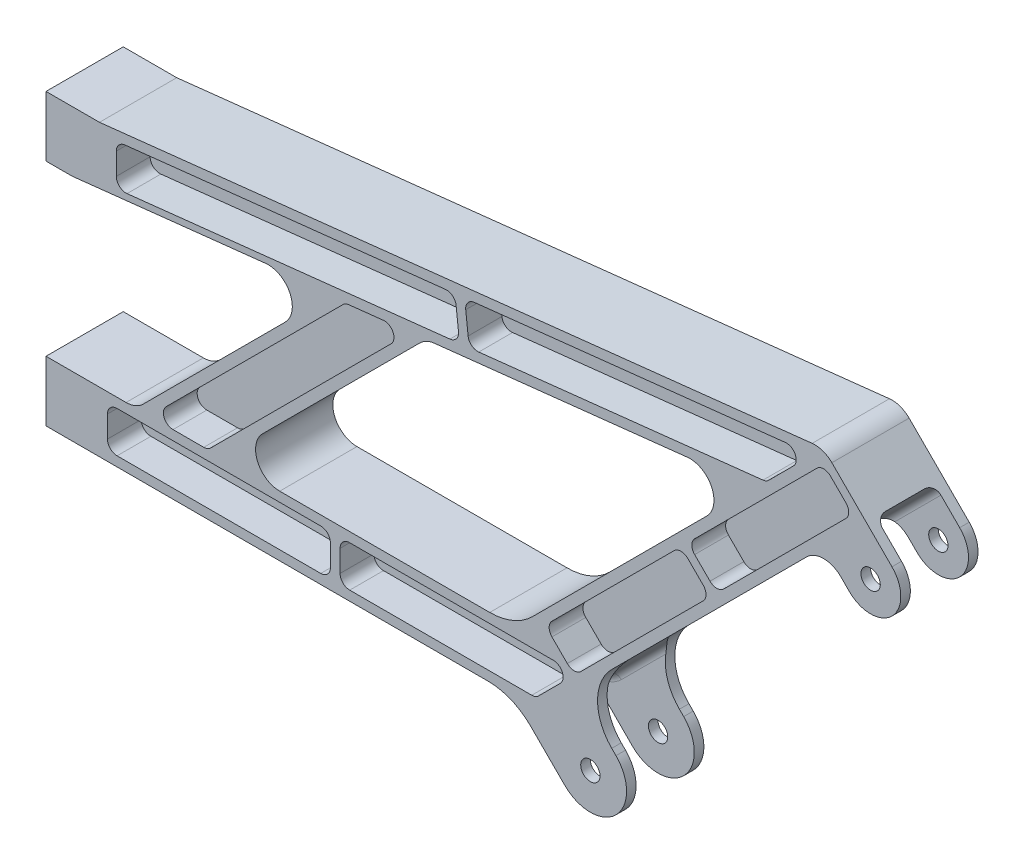
SolidWorks part; units mm, degrees
material "6061-T6 (SS)"
ref_plane "Front Plane" through (0, 0, 0) normal (0, 0, 1) x (1, 0, 0)
ref_plane "Top Plane" through (0, 0, 0) normal (0, 1, 0) x (1, 0, 0)
ref_plane "Right Plane" through (0, 0, 0) normal (1, 0, 0) x (0, 0, -1)
sketch "Sketch1" plane through (0, 0, 0) normal (0, 0, 1) x (1, 0, 0)
  line L1 (-157.7639, -90.8401) -> (-244.7728, -90.8401)
  line L2 (-67.8181, -11.2496) -> (-140.0863, -83.5177)
  line L3 (-16.0497, 33.7315) -> (8.8396, 8.8381)
  line L4 (-12.3744, -5.3033) -> (-8.8388, -8.8388)
  line L5 (-26.5165, -5.3033) -> (-107.2487, -86.0355)
  line L6 (-140.8326, -123.1624) -> (-126.6942, -137.3008)
  line L7 (-158.5102, -115.8401) -> (-341.1373, -115.8401)
  line L8 (-341.1373, -115.8401) -> (-341.1373, -90.8401)
  line L9 (-308.4124, -90.8401) -> (-341.1373, -90.8401)
  line L11 (-341.5776, -20.8403) -> (-331.2717, -20.8403)
  line L12 (-341.5776, -20.8403) -> (-341.5776, 4.1597)
  line L13 (-341.5776, 4.1597) -> (-319.4176, 4.1597)
  line L14 (-107.2487, -114.3198) -> (-105.481, -116.0876)
  line L15 (-319.4176, 4.1597) -> (-24.2138, 36.6012)
  line L17 (-301.3413, -87.9111) -> (-242.4814, -29.0512)
  line L18 (-75.9816, 5.7616) -> (-180.7131, -5.7479)
  line L19 (-251.8438, -73.769) -> (-186.6918, -8.6169)
  line L20 (-250.6448, -12.04) -> (-330.1793, -20.7804)
  arc A4 (8.8388, -8.8388) -> (8.8396, 8.8381) centre (0, 0) ccw
  arc A5 (-8.8388, -8.8388) -> (8.8388, -8.8388) centre (0, 0) ccw
  arc A6 (-12.3744, -5.3033) -> (-26.5165, -5.3033) centre (-19.4454, -12.3744) ccw
  arc A7 (-107.2487, -86.0355) -> (-107.2487, -114.3198) centre (-93.1066, -100.1777) ccw
  arc A8 (-105.481, -137.3008) -> (-105.481, -116.0876) centre (-116.0876, -126.6942) ccw
  arc A9 (-126.6942, -137.3008) -> (-105.481, -137.3008) centre (-116.0876, -126.6942) ccw
  circle A12 centre (-116.0876, -126.6942) radius 4
  circle A13 centre (0, 0) radius 4
  arc A15 (-158.5102, -115.8401) -> (-140.8326, -123.1624) centre (-158.5102, -140.8401) cw
  arc A16 (-157.7639, -90.8401) -> (-140.0863, -83.5177) centre (-157.7639, -65.8401) ccw
  arc A20 (-67.8181, -11.2496) -> (-75.9816, 5.7616) centre (-74.8892, -4.1785) ccw
  arc A21 (-16.0497, 33.7315) -> (-24.2138, 36.6012) centre (-23.1214, 26.661) ccw
  arc A22 (-186.6918, -8.6169) -> (-180.7131, -5.7479) centre (-179.6207, -15.688) cw
  arc A23 (-244.7728, -90.8401) -> (-251.8438, -73.769) centre (-244.7728, -80.8401) cw
  arc A24 (-330.1793, -20.7804) -> (-331.2717, -20.8403) centre (-331.2717, -10.8403) cw
  arc A25 (-308.4124, -90.8401) -> (-301.3413, -87.9111) centre (-308.4124, -80.8401) ccw
  arc A26 (-250.6448, -12.04) -> (-242.4814, -29.0512) centre (-249.5525, -21.9802) cw
  dimension "D2" = 25
  dimension "D3" = 25
  dimension "D7" = 10
  dimension "D6" = 25
  dimension "D1" = 25
  dimension "D4" = 25
  dimension "D5" = 25
  dimension "D8" = 119.9998
extrude "Boss-Extrude1" add sketch "Sketch1" along normal blind 32
sketch "Sketch2" plane through (0, 0, 32) normal (0, 0, 1) x (1, 0, 0)
  line L0 (-107.2487, -86.0355) -> (-26.5165, -5.3033) construction
  line L1 (-137.5386, -110.6685) -> (-128.5386, -101.6685)
  line L2 (-131.367, -94.8401) -> (-215.77, -94.8401)
  line L3 (-67.8181, -11.2496) -> (-140.0863, -83.5177) construction
  line L4 (-107.2487, -86.0355) -> (-26.5165, -5.3033)
  line L5 (-67.8181, -11.2496) -> (-140.0863, -83.5177)
  line L6 (-22.272, 28.6397) -> (-72.893, -21.9813)
  line L7 (-119.9767, -93.1066) -> (-69.3575, -42.4874)
  line L8 (-131.9975, -86.7426) -> (-125.6335, -93.1066)
  line L9 (-10.2515, 22.275) -> (-16.6149, 28.6394)
  line L10 (-64.9897, -14.078) -> (-137.2579, -86.3462) construction
  line L11 (-110.0772, -83.2071) -> (-29.3449, -2.4749) construction
  line L12 (-341.1373, -115.8401) -> (-158.5102, -115.8401) construction
  line L13 (-341.1373, -115.8401) -> (-158.5102, -115.8401)
  line L14 (-312.1373, -111.8401) -> (-227.77, -111.8401)
  line L15 (-341.1373, -111.8401) -> (-158.5102, -111.8401) construction
  line L16 (-341.1373, -90.8401) -> (-341.1373, -115.8401) construction
  line L17 (-316.1373, -98.8401) -> (-316.1373, -107.8401)
  line L18 (-157.7639, -90.8401) -> (-244.7728, -90.8401) construction
  line L19 (8.8396, 8.8381) -> (-16.0497, 33.7315) construction
  line L20 (-140.8326, -123.1624) -> (-126.6942, -137.3008) construction
  line L21 (-65.1149, -38.2448) -> (-77.1357, -26.224) construction
  line L22 (-72.893, -27.6382) -> (-66.5291, -34.0022)
  line L23 (-75.7215, -30.4666) -> (-69.3575, -36.8306)
  line L24 (-81.3783, -30.4666) -> (-131.9975, -81.0858)
  line L25 (-60.8722, -34.0022) -> (-10.2517, 16.6183)
  line L26 (-221.77, -94.8401) -> (-221.77, -111.8401) construction
  line L27 (-219.77, -98.8401) -> (-219.77, -107.8401)
  line L28 (-223.77, -98.8401) -> (-223.77, -107.8401)
  line L29 (-215.77, -111.8401) -> (-140.367, -111.8401)
  line L30 (-227.77, -94.8401) -> (-312.1373, -94.8401)
  line L38 (-308.8907, 1.2925) -> (-176.1091, 15.8845)
  line L39 (-24.2138, 36.6012) -> (-319.4176, 4.1597) construction
  line L40 (-308.0168, -15.7138) -> (-174.2521, -1.0137)
  line L41 (-75.9816, 5.7616) -> (-180.7131, -5.7479) construction
  line L42 (-312.4538, -2.6836) -> (-312.4538, -11.7378)
  line L43 (-32.0118, 24.5568) -> (-42.1838, 14.3847)
  line L44 (-170.145, 16.5399) -> (-168.288, -0.3583) construction
  line L45 (-171.6961, 12.3454) -> (-170.713, 3.3993)
  line L46 (-167.7201, 12.7824) -> (-166.7369, 3.8362)
  line L47 (-164.181, 17.1954) -> (-35.2771, 31.3613)
  line L48 (-162.3239, 0.2971) -> (-44.5753, 13.2371)
  line L49 (-218.5658, -10.7925) -> (-291.7849, -84.0116)
  line L50 (-242.4814, -29.0512) -> (-301.3413, -87.9111) construction
  line L51 (-198.6096, -14.8779) -> (-273.4002, -89.6685)
  line L52 (-186.6918, -8.6169) -> (-251.8438, -73.769) construction
  line L53 (-216.1743, -9.6449) -> (-201.875, -8.0734)
  line L54 (-288.9565, -90.8401) -> (-276.2286, -90.8401)
  line L55 (-341.5776, 4.1597) -> (-341.5776, -20.8403) construction
  arc A0 (-22.272, 28.6397) -> (-16.6149, 28.6394) centre (-19.4436, 25.8113) cw
  arc A1 (-10.2517, 16.6183) -> (-10.2515, 22.275) centre (-13.0801, 19.4468) ccw
  arc A2 (-119.9767, -93.1066) -> (-125.6335, -93.1066) centre (-122.8051, -90.2782) cw
  arc A3 (-131.9975, -81.0858) -> (-131.9975, -86.7426) centre (-129.169, -83.9142) ccw
  arc A4 (-312.1373, -111.8401) -> (-316.1373, -107.8401) centre (-312.1373, -107.8401) cw
  arc A5 (-312.1373, -94.8401) -> (-316.1373, -98.8401) centre (-312.1373, -98.8401) ccw
  arc A6 (-140.367, -111.8401) -> (-137.5386, -110.6685) centre (-140.367, -107.8401) ccw
  arc A7 (-128.5386, -101.6685) -> (-131.367, -94.8401) centre (-131.367, -98.8401) ccw
  arc A8 (-75.7215, -30.4666) -> (-81.3783, -30.4666) centre (-78.5499, -33.295) ccw
  arc A9 (-69.3575, -36.8306) -> (-69.3575, -42.4874) centre (-72.1859, -39.659) cw
  arc A10 (-66.5291, -34.0022) -> (-60.8722, -34.0022) centre (-63.7006, -31.1737) ccw
  arc A11 (-72.893, -27.6382) -> (-72.893, -21.9813) centre (-70.0646, -24.8098) cw
  arc A12 (-223.77, -107.8401) -> (-227.77, -111.8401) centre (-227.77, -107.8401) cw
  arc A13 (-219.77, -107.8401) -> (-215.77, -111.8401) centre (-215.77, -107.8401) ccw
  arc A14 (-219.77, -98.8401) -> (-215.77, -94.8401) centre (-215.77, -98.8401) cw
  arc A15 (-223.77, -98.8401) -> (-227.77, -94.8401) centre (-227.77, -98.8401) ccw
  arc A20 (-44.5753, 13.2371) -> (-42.1838, 14.3847) centre (-45.0122, 17.2132) ccw
  arc A21 (-35.2771, 31.3613) -> (-32.0118, 24.5568) centre (-34.8402, 27.3852) cw
  arc A22 (-166.7369, 3.8362) -> (-162.3239, 0.2971) centre (-162.7609, 4.2732) ccw
  arc A23 (-167.7201, 12.7824) -> (-164.181, 17.1954) centre (-163.744, 13.2193) cw
  arc A24 (-170.713, 3.3993) -> (-174.2521, -1.0137) centre (-174.6891, 2.9623) cw
  arc A25 (-171.6961, 12.3454) -> (-176.1091, 15.8845) centre (-175.6722, 11.9085) ccw
  arc A26 (-308.0168, -15.7138) -> (-312.4538, -11.7378) centre (-308.4538, -11.7378) cw
  arc A27 (-308.8907, 1.2925) -> (-312.4538, -2.6836) centre (-308.4538, -2.6836) ccw
  arc A28 (-198.6096, -14.8779) -> (-201.875, -8.0734) centre (-201.438, -12.0495) ccw
  arc A29 (-218.5658, -10.7925) -> (-216.1743, -9.6449) centre (-215.7374, -13.6209) cw
  arc A30 (-273.4002, -89.6685) -> (-276.2286, -90.8401) centre (-276.2286, -86.8401) cw
  arc A31 (-288.9565, -90.8401) -> (-291.7849, -84.0116) centre (-288.9565, -86.8401) cw
  point P34 (-316.1373, -111.8401)
  point P53 (-78.5499, -27.6382)
  point P58 (-63.7006, -36.8306)
  point P69 (-223.77, -111.8401)
  point P72 (-219.77, -111.8401)
  point P75 (-219.77, -94.8401)
  point P78 (-223.77, -94.8401)
  point P117 (-166.3, -0.1398)
  point P120 (-168.157, 16.7584)
  point P123 (-170.276, -0.5768)
  point P126 (-172.1331, 16.3215)
  dimension "D2" = 4
  dimension "D6" = 4
  dimension "D11" = 4
  dimension "D13" = 4
  dimension "D16" = 4
  dimension "D22" = 4
  dimension "D19" = 4
  dimension "D4" = 25
  dimension "D5" = 4
  dimension "D7" = 4
  dimension "D8" = 4
  dimension "D9" = 32
  dimension "D10" = 2
  dimension "D12" = 2
  dimension "D14" = 4
  dimension "D15" = 4
  dimension "D17" = 4
  dimension "D18" = 4
  dimension "D20" = 4
  dimension "D21" = 2
  dimension "D23" = 4
  dimension "D1" = 4
  dimension "D3" = 4
extrude "Cut-Extrude1" cut sketch "Sketch2" against normal blind 14 contours L38 A27 L42 A26 L40 A24 L45 A25 | A23 L46 A22 L48 A20 L43 A21 L47 | A31 L54 A30 L51 A28 L53 A29 L49 | A11 L22 A10 L25 A1 L9 A0 L6 | A9 L23 A8 L24 A3 L8 A2 L7 | A14 L27 A13 L29 A6 L1 A7 L2 | L28 A15 L30 A5 L17 A4 L14 A12
ref_plane "Plane1" through (0, 0, 16) normal (0, 0, 1) x (1, 0, 0)
mirror "Mirror1" about plane through (0, 0, 16) normal (0, 0, 1) of "Cut-Extrude1"
sketch "Sketch3" plane through (0, 0, 16) normal (0, 0, 1) x (1, 0, 0)
  line L0 (-158.5102, -115.8401) -> (-141.1954, -115.8401)
  line L1 (-98.969, -77.7558) -> (-134.1243, -112.9111)
  line L2 (-107.2487, -86.0355) -> (-26.5165, -5.3033) construction
  line L3 (-158.5102, -115.8401) -> (-116.5971, -149.2186)
  line L4 (-116.5971, -149.2186) -> (-66.3597, -110.0186)
  line L5 (-66.3597, -110.0186) -> (-98.969, -77.7558)
  line L6 (-29.0156, -7.8024) -> (7.8698, 29.083)
  line L7 (7.8698, 29.083) -> (26.3533, -15.3879)
  line L8 (26.3533, -15.3879) -> (-12.041, -17.819)
  line L9 (-12.041, -17.819) -> (-29.0156, -7.8024)
  arc A0 (-134.1243, -112.9111) -> (-141.1954, -115.8401) centre (-141.1954, -105.8401) cw
  dimension "D1" = 10
extrude "Cut-Extrude2" cut sketch "Sketch3" against normal blind 12.0515 and the other way blind 12.0515
sketch "Sketch5" plane through (0, 0, 16) normal (0, 0, 1) x (1, 0, 0)
  line L0 (0, -24.7236) -> (0, -90.9031)
fillet "Fillet1" radius 4 2 edges at (-14.1417, 7.0715, 28.0515) (-14.1417, 7.0715, 3.9485)
fillet "Fillet2" radius 4 6 edges at (-149.8528, -115.8401, 3.9485) (-137.3686, -115.0789, 3.9485) (-149.8528, -115.8401, 28.0515) (-137.3686, -115.0789, 28.0515) (-120.6865, -99.4733, 3.9485) (-120.6865, -99.4733, 28.0515)
sketch "Sketch6" plane through (-341.1373, 0, 0) normal (-1, 0, 0) x (0, 0, 1)
  line L4 (0, -90.8401) -> (0, -115.8401)
  line L5 (0, -115.8401) -> (32, -115.8401)
  line L6 (32, -115.8401) -> (32, -90.8401)
  line L7 (32, -90.8401) -> (0, -90.8401)
  line L8 (0, -90.8401) -> (0, -115.8401)
  line L9 (0, -115.8401) -> (32, -115.8401)
  line L10 (32, -115.8401) -> (32, -90.8401)
  line L11 (32, -90.8401) -> (0, -90.8401)
  dimension "D1" = 0
extrude "Boss-Extrude2" add sketch "Sketch6" along normal up to surface (0.4403 mm away)
